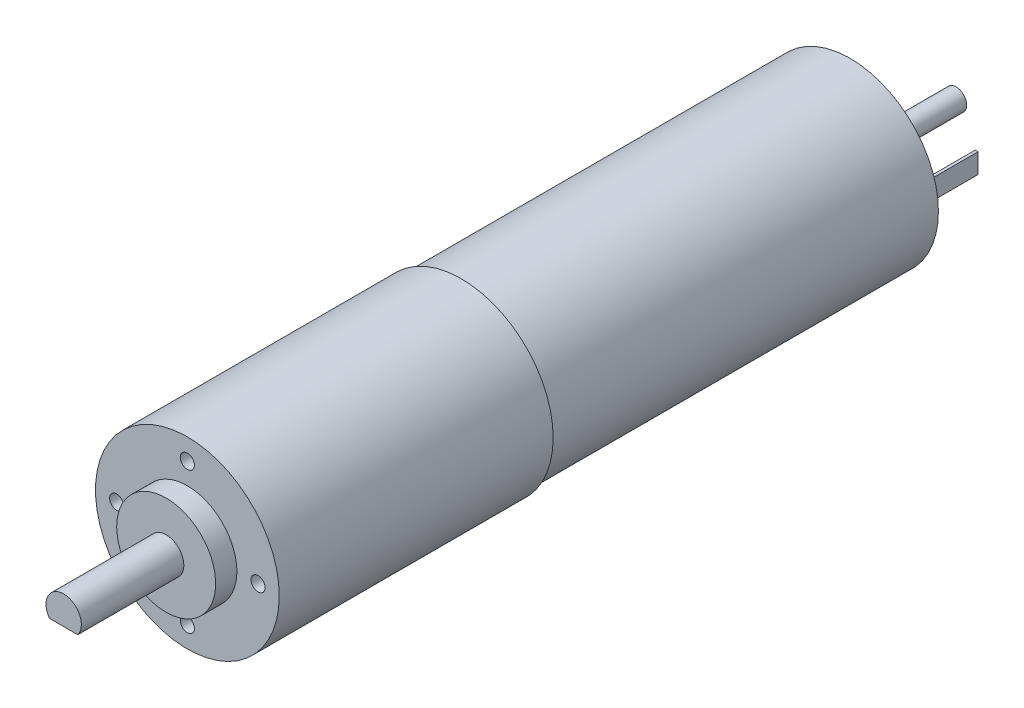
SolidWorks part; units mm, degrees
ref_plane "Front Plane" through (0, 0, 0) normal (0, 0, 1) x (1, 0, 0)
ref_plane "Top Plane" through (0, 0, 0) normal (0, 1, 0) x (1, 0, 0)
ref_plane "Right Plane" through (0, 0, 0) normal (1, 0, 0) x (0, 0, -1)
ref_plane "Plane1"
sketch "Sketch1" plane through (0, 0, 0) normal (0, 0, 1) x (1, 0, 0)
  circle A0 centre (0, 0) radius 12.5
  dimension "D1" = 25
extrude "Extrusion1" add sketch "Sketch1" along normal blind 55
sketch "Sketch2" plane through (0, 0, 55) normal (0, 0, 1) x (1, 0, 0)
  circle A0 centre (0, 0) radius 13
extrude "Extrusion2" add sketch "Sketch2" along normal blind 38.75
sketch "Sketch3" plane through (0, 0, 93.75) normal (0, 0, 1) x (1, 0, 0)
  circle A0 centre (0, 0) radius 7
  dimension "D1" = 14
extrude "Extrusion3" add sketch "Sketch3" along normal blind 3
sketch "Sketch4" plane through (0, 0, 96.75) normal (0, 0, 1) x (1, 0, 0)
  circle A0 centre (0, 0) radius 2.5
  dimension "D1" = 5
extrude "Extrusion4" add sketch "Sketch4" along normal blind 14.5
ref_plane "Plane2"
sketch "Sketch5" plane through (0, 0, 93.75) normal (0, 0, 1) x (1, 0, 0)
  circle A0 centre (0, 10) radius 1
  circle A1 centre (10, 0) radius 1
  circle A2 centre (0, -10) radius 1
  circle A3 centre (-10, 0) radius 1
  dimension "D1" = 2
  dimension "D2" = 2
  dimension "D3" = 2
  dimension "D4" = 2
extrude "Extrusion5" cut sketch "Sketch5" against normal blind 4 contours A0 | A1 | A2 | A3
sketch "Sketch6" plane through (0, 0, 0) normal (0, 0, -1) x (-1, 0, 0)
  circle A0 centre (0, 0) radius 4
  dimension "D1" = 8
extrude "Extrusion6" add sketch "Sketch6" along normal blind 2.75
ref_plane "Plane3"
sketch "Sketch7" plane through (0, 0, 0) normal (0, 0, -1) x (-1, 0, 0)
  circle A0 centre (0, 0) radius 1.5
  dimension "D1" = 3
extrude "Extrusion7" add sketch "Sketch7" along normal blind 15
ref_plane "Plane4"
sketch "Sketch8" plane through (0, 0, 0) normal (0, 0, -1) x (-1, 0, 0)
  line L0 (9, 1.4) -> (9.4, 1.4)
  line L1 (9.4, 1.4) -> (9.4, -1.4)
  line L2 (9.4, -1.4) -> (9, -1.4)
  line L3 (9, -1.4) -> (9, 1.4)
  line L4 (-9, 1.4) -> (-9.4, 1.4)
  line L5 (-9.4, 1.4) -> (-9.4, -1.4)
  line L6 (-9.4, -1.4) -> (-9, -1.4)
  line L7 (-9, -1.4) -> (-9, 1.4)
  dimension "D1" = 2.8
  dimension "D2" = 0.4
  dimension "D3" = 2.8
extrude "Extrusion8" add sketch "Sketch8" along normal blind 8.7 contours L3 L2 L1 L0 | L6 L7 L4 L5
sketch "Sketch9" plane through (0, 0, 111.25) normal (0, 0, 1) x (1, 0, 0)
  line L0 (2, -1.5) -> (-2, -1.5)
  circle A0 centre (0, 0) radius 2.5
  circle M2 centre (0, 0) radius 2.5
  dimension "D2" = 5
  dimension "D1" = 1.5
extrude "Cut-Extrude1" cut sketch "Sketch9" against normal blind 10 contours L0 M2
